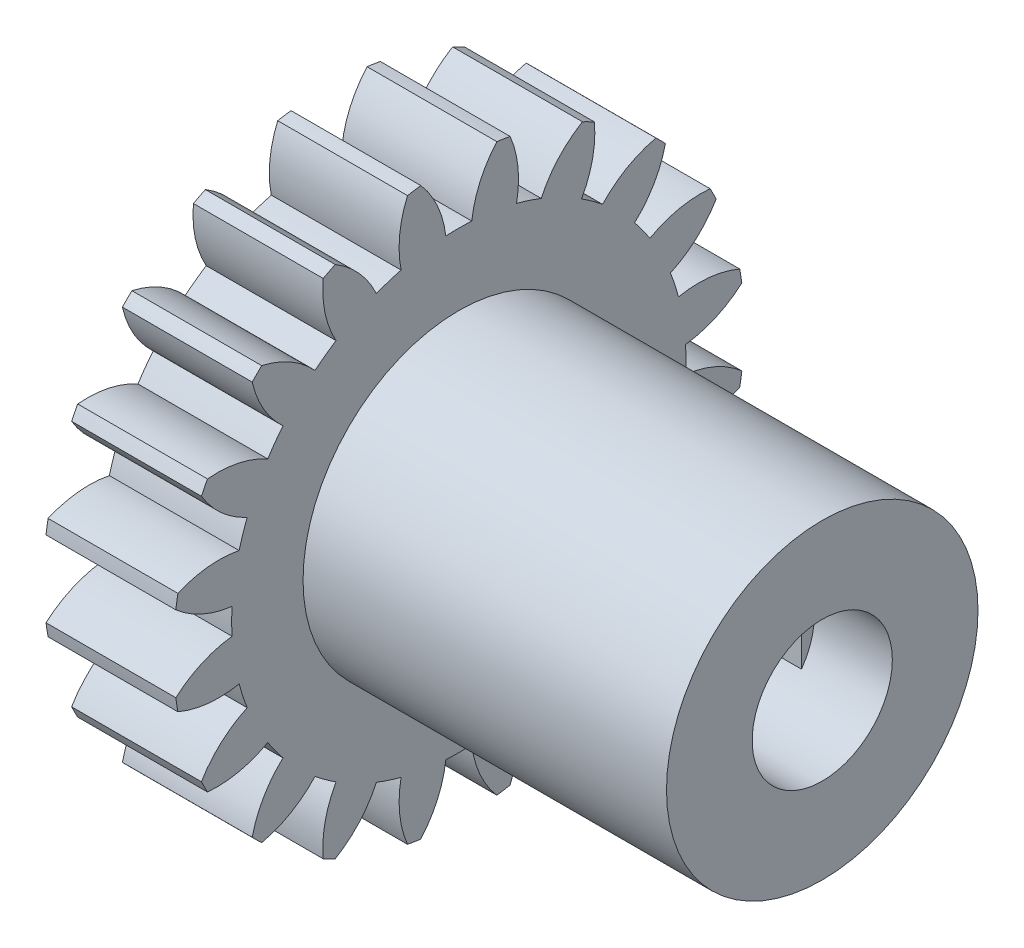
SolidWorks part; units mm, degrees
ref_plane "Plane1" through (0, 0, 0) normal (0, 0, 1) x (1, 0, 0)
ref_plane "Plane2" through (0, 0, 0) normal (0, 1, 0) x (1, 0, 0)
ref_plane "Plane3" through (0, 0, 0) normal (1, 0, 0) x (0, 0, -1)
sketch "HoldingSke" plane through (0, 0, 0) normal (0, 1, 0) x (1, 0, 0)
  line L0 (0, 0) -> (0.9397, -0.342)
  line L1 (-15, 0) -> (100, 0) construction
  line L2 (0, 0) -> (-2.1039, 2.3779)
  line L3 (0, 0) -> (-11.863, 4.5341)
  line L4 (0, 0) -> (8.1152, 2.9537)
  line L5 (0, 0) -> (-46.8476, -17.4728)
  line L6 (0, 0) -> (-8.2896, -5.593)
  line L7 (-2.1039, 2.3779) -> (8.6586, 51.2059)
  line L8 (-76.2, 54.61) -> (-75.7, 54.61)
  line L9 (-71.009, 38.7566) -> (-53.1078, 45.2721)
  line L10 (-76.2, 71.12) -> (104.1128, 71.12)
  line L11 (0, 0) -> (-10, 0)
  line L12 (-76.2, 101.6) -> (-76.162, 101.6)
  line L13 (24.9733, 27.94) -> (52.9518, 28.4284)
  line L14 (24.9733, 27.94) -> (24.9743, 27.94)
  line L15 (24.9733, 27.94) -> (100.4006, 29.5858)
  line L16 (-63.627, -1) -> (-12.827, -1)
  circle A0 centre (0, 0) radius 1.5
  circle A1 centre (0, 0) radius 8.749
  circle A2 centre (0, 0) radius 37.5
  circle A3 centre (0, 0) radius 1.5
  dimension "MHD" = 17.498
  dimension "Hub_dia" = 75
  dimension "Bore" = 3
  dimension "MBD" = 3
  dimension "Num_teeth" = 20
  dimension "Pitch" = 1
  dimension "Overall_len" = 50
  dimension "Show_teeth" = 20
  dimension "Thickness" = 10
  dimension "OAL" = 50.0001
  dimension "T_dim" = 0.5
  dimension "Ap" = 20
  dimension "H" = 19.05
  dimension "Pitch_radius" = 180.3128
  dimension "Width" = 10
  dimension "Backlash" = 0.038
  dimension "Addendum_fac" = 1
  dimension "Dedendum_fac" = 1.25
  dimension "Clearance_fac" = 0.25
  dimension "Dedendum_add" = 0.001
  dimension "Module" = 1
sketch "BasProSke" plane through (0, 0, 0) normal (0, 1, 0) x (1, 0, 0)
  line L0 (-10, 0) -> (60, 0) construction
  line L1 (0, 0) -> (0, 11)
  line L2 (0, 0) -> (5, 0)
  line L3 (5, 0) -> (5, 11)
  line L4 (5, 11) -> (0, 11)
  dimension "Thickness" = 5
  dimension "Diameter" = 22
revolve "Base-Revolve" add sketch "BasProSke" angle 360 about L0
sketch "TooCutSke" plane through (0, 0, 0) normal (1, 0, 0) x (0, 0, -1)
  line L1 (0, 0) -> (0, 107) construction
  line L2 (0, 0) -> (-0.8511, 9.9637) construction
  line L3 (0, 0) -> (-3.1206, 19.7028) construction
  line L4 (-0.8511, 9.9637) -> (-1.5603, 9.8514) construction
  arc A0 (0.4999, 8.7347) -> (-0.4999, 8.7347) centre (0, 0) ccw
  arc A1 (1.4852, 10.9249) -> (-1.4852, 10.9249) centre (0, 0) ccw
  circle A2 centre (0, 0) radius 10 construction
  circle A3 centre (0, 0) radius 9.3969 construction
  arc A4 (-0.4999, 8.7347) -> (-1.4852, 10.9249) centre (-4.4722, 8.2645) ccw
  arc A5 (1.4852, 10.9249) -> (0.4999, 8.7347) centre (4.4722, 8.2645) ccw
  dimension "Root_dia" = 17.498
  dimension "Overcut_dia" = 22.0508
  dimension "Pitch_dia" = 20
  dimension "Base_dia" = 18.7939
  dimension "Flank_rad" = 4
  dimension "Half_ang" = 9
  dimension "Half_CT" = 0.7181
extrude "ToothCut" cut sketch "TooCutSke" along normal through all
fillet "Breaks" [suppressed] radius 0.02
fillet "RootFillets" [suppressed] radius 0.251
pattern_circular "TeethCuts" count 20 over 360 about axis through (0, 0, 0) along (1, 0, 0) of "ToothCut", "RootFillets", "Breaks"
sketch "HubNeaOneSke" plane through (0, 0, 0) normal (-1, 0, 0) x (0, 0, 1)
  circle A0 centre (0, 0) radius 8.749
  dimension "Diameter" = 17.498
extrude "HubNearOne" [suppressed] add sketch "HubNeaOneSke" along normal blind 45.0001
sketch "HubNeaBotSke" plane through (0, 0, 0) normal (-1, 0, 0) x (0, 0, 1)
  circle A0 centre (0, 0) radius 8.749
  dimension "Diameter" = 17.498
extrude "HubNearBoth" [suppressed] add sketch "HubNeaBotSke" along normal blind 22.5
ref_plane "FarPln" through (5, 0, 0) normal (1, 0, 0) x (0, 0, -1)
sketch "HubFarSke" plane through (5, 0, 0) normal (1, 0, 0) x (0, 0, -1)
  circle A0 centre (0, 0) radius 8.749
  dimension "Diameter" = 17.498
extrude "HubFar" [suppressed] add sketch "HubFarSke" along normal blind 22.5
sketch "BorSke" plane through (0, 0, 0) normal (1, 0, 0) x (0, 0, -1)
  circle A0 centre (0, 0) radius 1.5
  dimension "Diameter" = 3
extrude "Bore" cut sketch "BorSke" along normal mid plane 100.0001
sketch "KeySke" plane through (0, 0, 0) normal (1, 0, 0) x (0, 0, -1)
  line L0 (-0.6, 0) -> (-0.6, 2)
  line L1 (-0.6, 2) -> (0.6, 2)
  line L2 (0.6, 2) -> (0.6, 0)
  line L3 (0, 0) -> (0, 34) construction
  line L4 (-0.6, 0) -> (0.6, 0)
  dimension "Offset" = 2
  dimension "Width" = 1.2
extrude "Keyway" [suppressed] cut sketch "KeySke" along normal mid plane 100.0001
pattern_circular "Keyway2" [suppressed] count 2 every 90 about axis through (-10, 0, 0) along (1, 0, 0)
sketch "草图1" plane through (5, 0, 0) normal (1, 0, 0) x (0, 0, -1)
  circle A0 centre (0, 0) radius 6
  dimension "D1" = 12
extrude "凸台-拉伸1" add sketch "草图1" along normal blind 14
sketch "草图2" plane through (19, 0, 0) normal (1, 0, 0) x (0, 0, -1)
  line L0 (2.2, 1.5652) -> (2.2, -1.5652)
  arc A0 (2.2, 1.5652) -> (2.2, -1.5652) centre (0, 0) ccw
  dimension "D1" = 5.4
  dimension "D2" = 2.2
extrude "切除-拉伸1" cut sketch "草图2" against normal through all
sketch "草图3" plane through (19, 0, 0) normal (1, 0, 0) x (0, 0, -1)
  circle A0 centre (0, 0) radius 2.7
extrude "切除-拉伸2" cut sketch "草图3" against normal blind 3
equation "' \"Module@HoldingSke\" = 6.35"
equation "' \"Num_teeth@HoldingSke\" = 12"
equation "' \"Ap@HoldingSke\" =  20"
equation "' \"Ap@HoldingSke\" = 20"
equation "' \"Width@HoldingSke\" = 0.5 * 25.4"
equation "' \"Hub_dia@HoldingSke\"= 1 * 25.4"
equation "' \"Hub_dia@HoldingSke\" = 1 * 25.4"
equation "' \"Overall_len@HoldingSke\" = 1.0 * 25.4"
equation "' \"Bore@HoldingSke\" = 0.75 * 25.4"
equation "' \"T_dim@HoldingSke\" = 0.1 * 25.4"
equation "' \"Width@KeySke\" = 0.25 * 25.4"
equation "' \"Show_teeth@HoldingSke\" = 13"
equation "' \"Backlash@HoldingSke\" = 0.009 * 25.4"
equation "' \"Addendum_fac@HoldingSke\" = 1.0"
equation "' \"Dedendum_fac@HoldingSke\" = 1.25"
equation "' \"Dedendum_add@HoldingSke\" = 0.00005 * 25.4"
equation "' \"Clearance_fac@HoldingSke\" = 0.25"
equation "\"Pitch@HoldingSke\" = 1 / \"Module@HoldingSke\""
equation "\"Overcut_dia@TooCutSke\" = (\"Num_teeth@HoldingSke\" + 2 * \"Addendum_fac@HoldingSke\") / \"Pitch@HoldingSke\" + 0.002 * 25.4"
equation "\"Pitch_dia@TooCutSke\" = \"Num_teeth@HoldingSke\" / \"Pitch@HoldingSke\""
equation "\"Base_dia@TooCutSke\" = \"Num_teeth@HoldingSke\" / \"Pitch@HoldingSke\" * cos((\"Ap@HoldingSke\"  * 3.14159265 / 180))"
equation "\"Root_dia@TooCutSke\" = (\"Num_teeth@HoldingSke\" + 2) / \"Pitch@HoldingSke\" - 2 * (\"Addendum_fac@HoldingSke\" + \"Dedendum_fac@HoldingSke\") / \"Pitch@HoldingSke\" - \"Dedendum_add@HoldingSke\" * 2"
equation "\"Half_ang@TooCutSke\" = 180 / \"Num_teeth@HoldingSke\""
equation "\"Half_CT@TooCutSke\" = \"Num_teeth@HoldingSke\" / \"Pitch@HoldingSke\" * sin((3.14159265 / 2 / \"Num_teeth@HoldingSke\")) / 2 - 7 * \"Backlash@HoldingSke\" / 4"
equation "\"Flank_rad@TooCutSke\" = \"Num_teeth@HoldingSke\" / \"Pitch@HoldingSke\" / 5"
equation "\"Radius@RootFillets\" = \"Clearance_fac@HoldingSke\" / \"Pitch@HoldingSke\" + \"Dedendum_add@HoldingSke\""
equation "\"Break_rad@Breaks\" = 0.02 / \"Pitch@HoldingSke\""
equation "\"Thickness@HoldingSke\" = \"Width@HoldingSke\""
equation "\"OAL@HoldingSke\" = \"Thickness@HoldingSke\""
equation "\"MHD@HoldingSke\" = (\"Num_teeth@HoldingSke\" + 2) / \"Pitch@HoldingSke\" - 2 * (\"Addendum_fac@HoldingSke\" + \"Dedendum_fac@HoldingSke\")  / \"Pitch@HoldingSke\" - \"Dedendum_add@HoldingSke\" * 2"
equation "\"MBD@HoldingSke\" = (\"Num_teeth@HoldingSke\" + 2) / \"Pitch@HoldingSke\" - 2 * (\"Addendum_fac@HoldingSke\" + \"Dedendum_fac@HoldingSke\")  / \"Pitch@HoldingSke\" - \"Dedendum_add@HoldingSke\" * 2 - 0.002 * 25.4"
equation "\"MHD@HoldingSke\" = ((sgn( \"MHD@HoldingSke\" - \"Hub_dia@HoldingSke\" )-1)*( \"MHD@HoldingSke\" - \"Hub_dia@HoldingSke\" ))/-2+ \"Hub_dia@HoldingSke\""
equation "\"MBD@HoldingSke\" = ((sgn( \"MBD@HoldingSke\" - \"Bore@HoldingSke\" )-1)*( \"MBD@HoldingSke\" - \"Bore@HoldingSke\" ))/-2+ \"Bore@HoldingSke\""
equation "\"OAL@HoldingSke\" = ((sgn( \"OAL@HoldingSke\" - \"Overall_len@HoldingSke\" )+1)*( \"OAL@HoldingSke\" - \"Overall_len@HoldingSke\" ))/2 + \"Overall_len@HoldingSke\" + 0.000002 * 25.4"
equation "\"Num_teeth@TeethCuts\" = int( \"Show_teeth@HoldingSke\" ) + 1"
equation "\"Num_teeth@TeethCuts\" = ((sgn( \"Num_teeth@TeethCuts\" - \"Num_teeth@HoldingSke\" )-1)*( \"Num_teeth@TeethCuts\" - \"Num_teeth@HoldingSke\" ))/-2+ \"Num_teeth@HoldingSke\""
equation "\"Num_teeth@TeethCuts\" = ((sgn( \"Num_teeth@TeethCuts\" - 2.0)+1)*( \"Num_teeth@TeethCuts\" - 2.0))/2 +2.0"
equation "\"Angle@TeethCuts\" = 360.0 / \"Num_teeth@HoldingSke\""
equation "\"Diameter@BasProSke\" = (\"Num_teeth@HoldingSke\" + 2 * \"Addendum_fac@HoldingSke\") / \"Pitch@HoldingSke\""
equation "' \"Fillet_rad@BasProSke\" =  \"Thickness@HoldingSke\" * 0.05"
equation "' \"Fillet_rad@BasProSke\" = \"Thickness@HoldingSke\" * 0.05"
equation "\"MHD@HoldingSke\" = ((sgn( \"MHD@HoldingSke\" - \"Root_dia@TooCutSke\" )-1)*( \"MHD@HoldingSke\" - \"Root_dia@TooCutSke\" ))/-2+ \"Root_dia@TooCutSke\""
equation "\"Diameter@HubNeaOneSke\" = \"MHD@HoldingSke\""
equation "\"Length@HubNearOne\" = \"OAL@HoldingSke\" - \"Thickness@BasProSke\""
equation "\"Diameter@HubNeaBotSke\" = \"MHD@HoldingSke\""
equation "\"Length@HubNearBoth\" = ( \"OAL@HoldingSke\" - \"Thickness@BasProSke\" ) / 2.0"
equation "\"Thickness@FarPln\" = \"Thickness@BasProSke\""
equation "\"Diameter@HubFarSke\" = \"MHD@HoldingSke\""
equation "\"Length@HubFar\" = ( \"OAL@HoldingSke\" - \"Thickness@BasProSke\" ) / 2.0"
equation "\"D1@Bore\" = \"OAL@HoldingSke\" * 2.0"
equation "\"D1@Keyway\" = \"OAL@HoldingSke\" * 2.0"
equation "\"Offset@KeySke\" = \"T_dim@HoldingSke\" + \"MBD@HoldingSke\" / 2.0"
